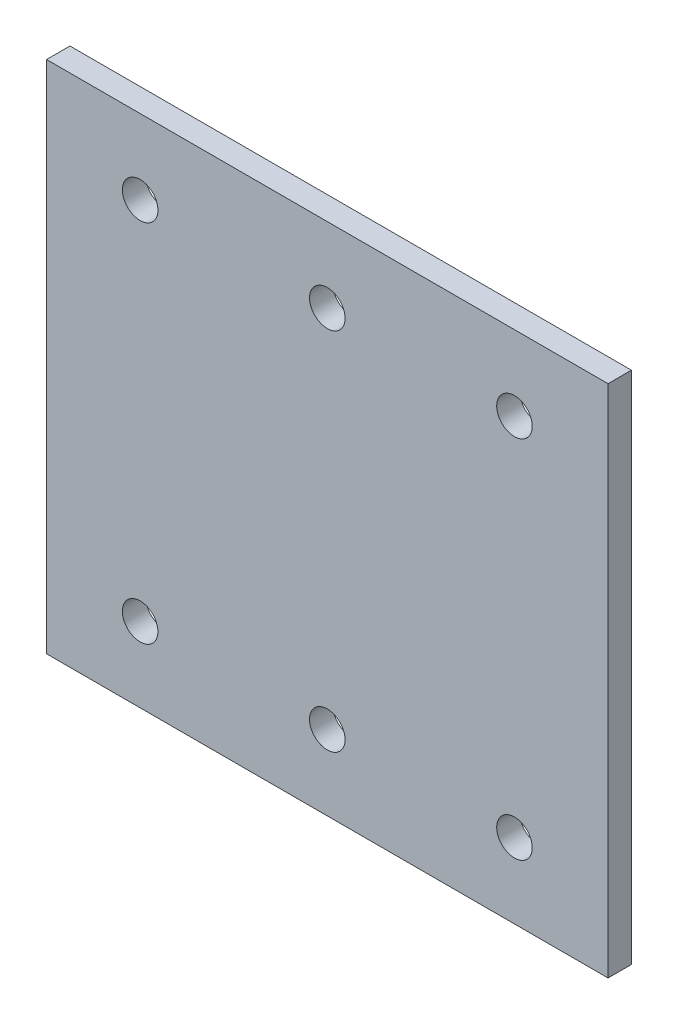
SolidWorks part; units mm, degrees
material "6061 Alloy"
ref_plane "Front Plane" through (0, 0, 0) normal (0, 0, 1) x (1, 0, 0)
ref_plane "Top Plane" through (0, 0, 0) normal (0, 1, 0) x (1, 0, 0)
ref_plane "Right Plane" through (0, 0, 0) normal (1, 0, 0) x (0, 0, -1)
sketch "Sketch1" plane through (0, 0, 0) normal (0, 0, 1) x (1, 0, 0)
  line L0 (38.1, 69.85) -> (38.1, 0) construction
  line L1 (0, 0) -> (76.2, 0)
  line L2 (0, 0) -> (0, 69.85)
  line L3 (0, 69.85) -> (76.2, 69.85)
  line L4 (76.2, 0) -> (76.2, 69.85)
  line L5 (0, 34.925) -> (76.2, 34.925) construction
  line L6 (12.7, 10.16) -> (12.7, 0) construction
  circle A0 centre (12.7, 59.69) radius 2.413
  circle A1 centre (38.1, 59.69) radius 2.413
  circle A2 centre (63.5, 59.69) radius 2.413
  circle A3 centre (63.5, 10.16) radius 2.413
  circle A4 centre (38.1, 10.16) radius 2.413
  circle A5 centre (12.7, 10.16) radius 2.413
  dimension "D3" = 4.826
  dimension "D1" = 69.85
  dimension "D2" = 76.2
  dimension "D4" = 12.7
  dimension "D6" = 10.16
  dimension "D5" = 3
extrude "Boss-Extrude1" add sketch "Sketch1" along normal blind 3.175
